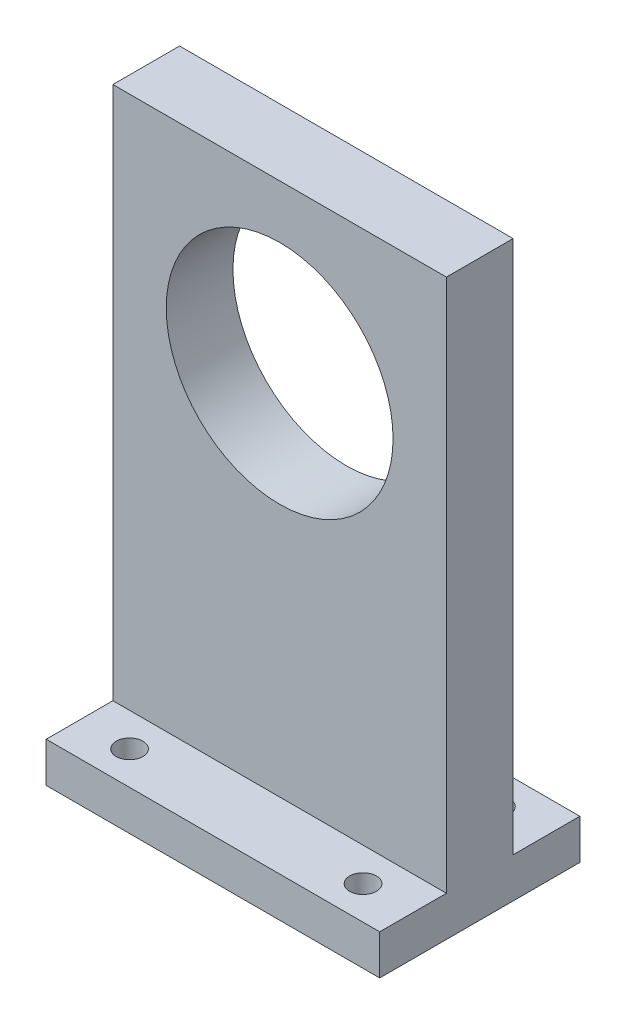
SolidWorks part; units mm, degrees
ref_plane "Front Plane" through (0, 0, 0) normal (0, 0, 1) x (1, 0, 0)
ref_plane "Top Plane" through (0, 0, 0) normal (0, 1, 0) x (1, 0, 0)
ref_plane "Right Plane" through (0, 0, 0) normal (1, 0, 0) x (0, 0, -1)
sketch "Sketch1" plane through (0, 0, 0) normal (0, 1, 0) x (1, 0, 0)
  line L1 (-12.5, -7.5) -> (12.5, -7.5)
  line L2 (-12.5, -7.5) -> (-12.5, 7.5)
  line L3 (-12.5, 7.5) -> (12.5, 7.5)
  line L4 (12.5, -7.5) -> (12.5, 7.5)
  line L5 (-12.5, -7.5) -> (12.5, 7.5) construction
  line L6 (-12.5, 7.5) -> (12.5, -7.5) construction
  point P0 (0, 0)
  dimension "D1" = 25
  dimension "D2" = 15
extrude "Boss-Extrude1" add sketch "Sketch1" along normal blind 3
sketch "Sketch2" plane through (0, 3, 0) normal (0, 1, 0) x (1, 0, 0)
  line L0 (12.5, -7.5) -> (12.5, 7.5) construction
  line L1 (-12.5, -2.5) -> (12.5, -2.5)
  line L2 (-12.5, -2.5) -> (-12.5, 2.5)
  line L3 (-12.5, 2.5) -> (12.5, 2.5)
  line L4 (12.5, -2.5) -> (12.5, 2.5)
  line L5 (-12.5, -2.5) -> (12.5, 2.5) construction
  line L6 (-12.5, 2.5) -> (12.5, -2.5) construction
  point P0 (0, 0)
  dimension "D1" = 5
extrude "Boss-Extrude2" add sketch "Sketch2" along normal blind 40
sketch "Sketch3" plane through (0, 3, 0) normal (0, 1, 0) x (1, 0, 0)
  line L0 (-12.5, 7.5) -> (-12.5, 2.5) construction
  line L1 (12.5, 2.5) -> (12.5, 7.5) construction
  line L2 (12.5, 7.5) -> (-12.5, 7.5) construction
  circle A0 centre (-8.75, 5) radius 1
  circle A1 centre (8.75, 5) radius 1
  point P6 (-12.5, 5)
  point P9 (12.5, 5)
  point P10 (0, 0)
  dimension "D5" = 2
  dimension "D6" = 2
  dimension "D1" = 3.75
  dimension "D2" = 3.75
  dimension "D3" = 2.5
  dimension "D4" = 2.5
extrude "Cut-Extrude1" cut sketch "Sketch3" against normal through all
mirror "Mirror1" about plane through (0, 0, 0) normal (0, 0, 1) of "Cut-Extrude1"
sketch "Sketch4" plane through (0, 0, 2.5) normal (0, 0, 1) x (1, 0, 0)
  line L0 (-12.5, 43) -> (12.5, 43) construction
  line L1 (12.5, 43) -> (12.5, 3) construction
  circle A0 centre (0, 30.5) radius 8.5
  point P4 (0, 0)
  dimension "D1" = 17
  dimension "D2" = 12.5
  dimension "D3" = 12.5
extrude "Cut-Extrude2" cut sketch "Sketch4" against normal through all
